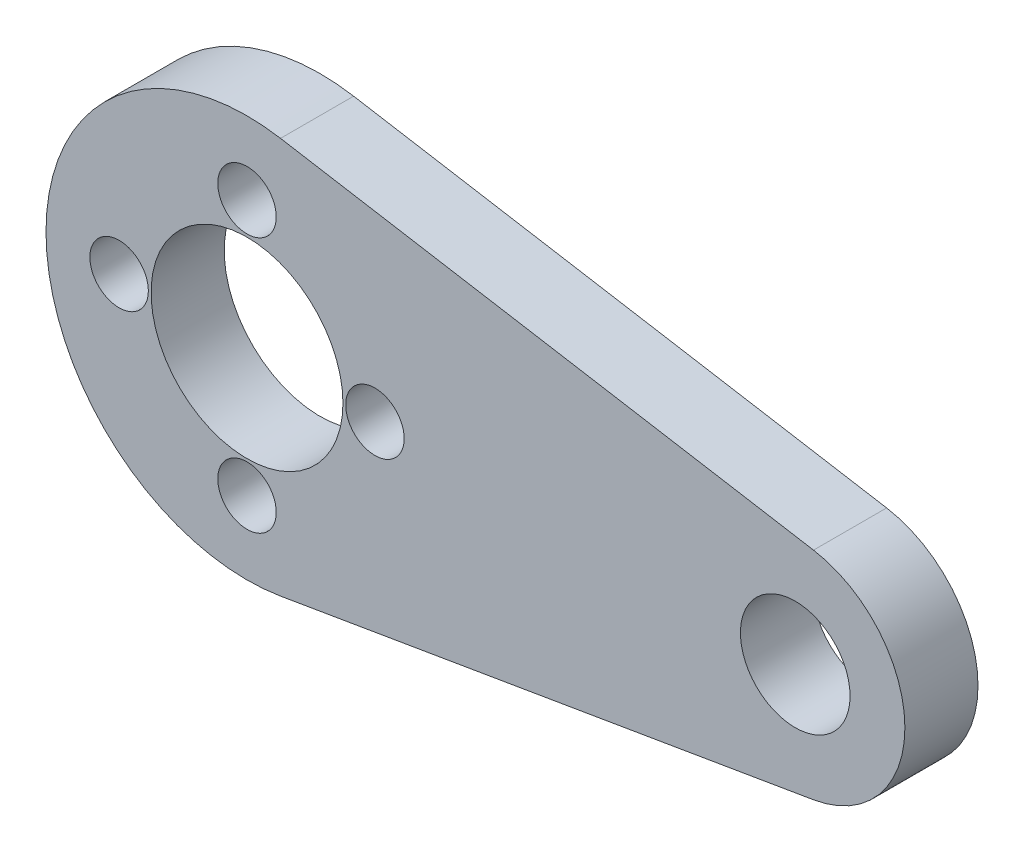
SolidWorks part; units mm, degrees
material "玻纤"
ref_plane "前视基准面" through (0, 0, 0) normal (0, 0, 1) x (1, 0, 0)
ref_plane "上视基准面" through (0, 0, 0) normal (0, 1, 0) x (1, 0, 0)
ref_plane "右视基准面" through (0, 0, 0) normal (1, 0, 0) x (0, 0, -1)
sketch "草图1" plane through (0, 0, 0) normal (0, 0, 1) x (1, 0, 0)
  line L0 (0, 0) -> (30, 0) construction
  line L3 (1.8333, 10.8461) -> (31, 5.9161)
  line L4 (1.8333, -10.8461) -> (31, -5.9161)
  circle A2 centre (0, 0) radius 7 construction
  circle A3 centre (0, 7) radius 1.6
  circle A4 centre (-7, 0) radius 1.6
  circle A5 centre (0, -7) radius 1.6
  circle A6 centre (7, 0) radius 1.6
  arc A7 (1.8333, 10.8461) -> (1.8333, -10.8461) centre (0, 0) ccw
  circle A8 centre (30, 0) radius 3
  arc A9 (31, 5.9161) -> (31, -5.9161) centre (30, 0) cw
  dimension "D1" = 30
  dimension "D3" = 14
  dimension "D4" = 3.2
  dimension "D2" = 6
  dimension "D5" = 6
  dimension "D6" = 11
extrude "凸台-拉伸1" add sketch "草图1" along normal blind 4
sketch "草图4" plane through (0, 0, 4) normal (0, 0, 1) x (1, 0, 0)
  circle A0 centre (0, 0) radius 5.25
  dimension "D1" = 10.5
extrude "切除-拉伸3" cut sketch "草图4" against normal through all
